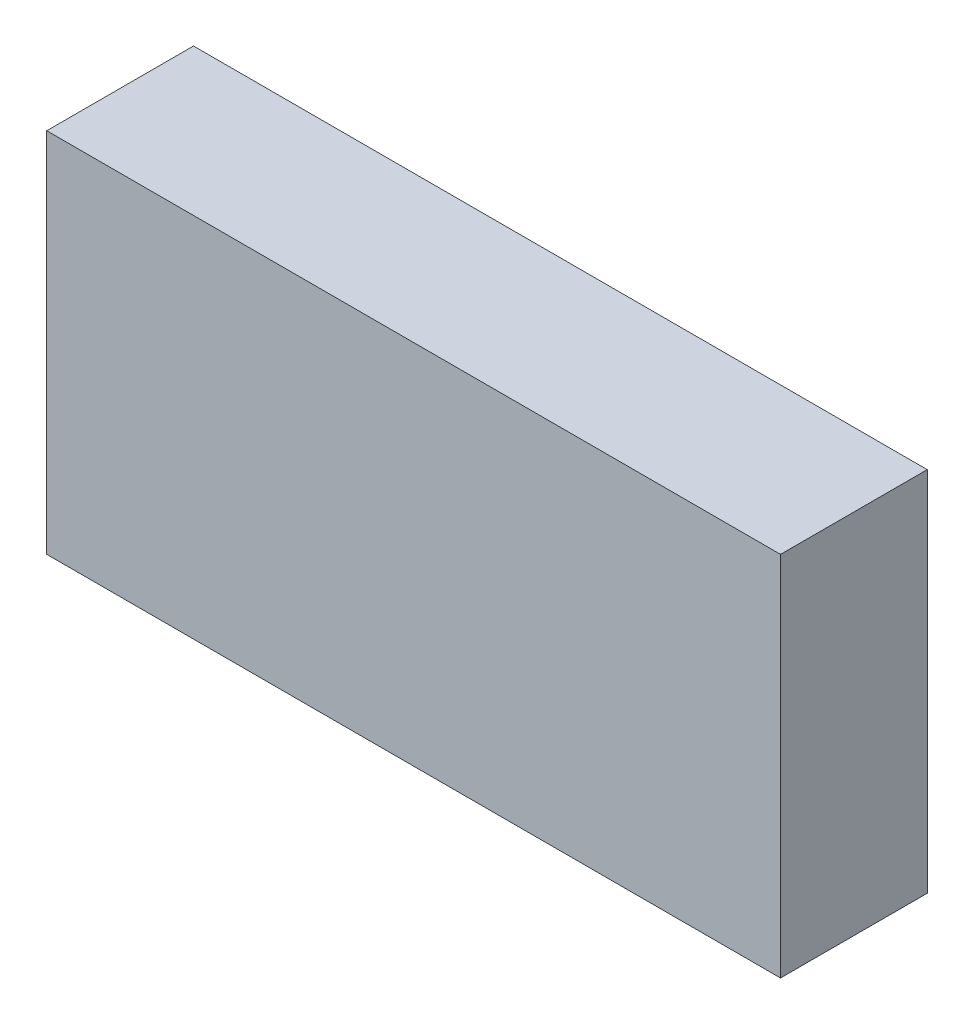
SolidWorks part; units mm, degrees
ref_plane "Alzado" through (0, 0, 0) normal (0, 0, 1) x (1, 0, 0)
ref_plane "Planta" through (0, 0, 0) normal (0, 1, 0) x (1, 0, 0)
ref_plane "Vista lateral" through (0, 0, 0) normal (1, 0, 0) x (0, 0, -1)
sketch "Croquis1" plane through (0, 0, 0) normal (0, 0, 1) x (1, 0, 0)
  line L1 (-50, 25) -> (50, 25)
  line L2 (-50, 25) -> (-50, -25)
  line L3 (-50, -25) -> (50, -25)
  line L4 (50, 25) -> (50, -25)
  dimension "D1" = 100
  dimension "D2" = 50
  dimension "D3" = 50
  dimension "D4" = 25
extrude "Saliente-Extruir1" add sketch "Croquis1" along normal blind 20
